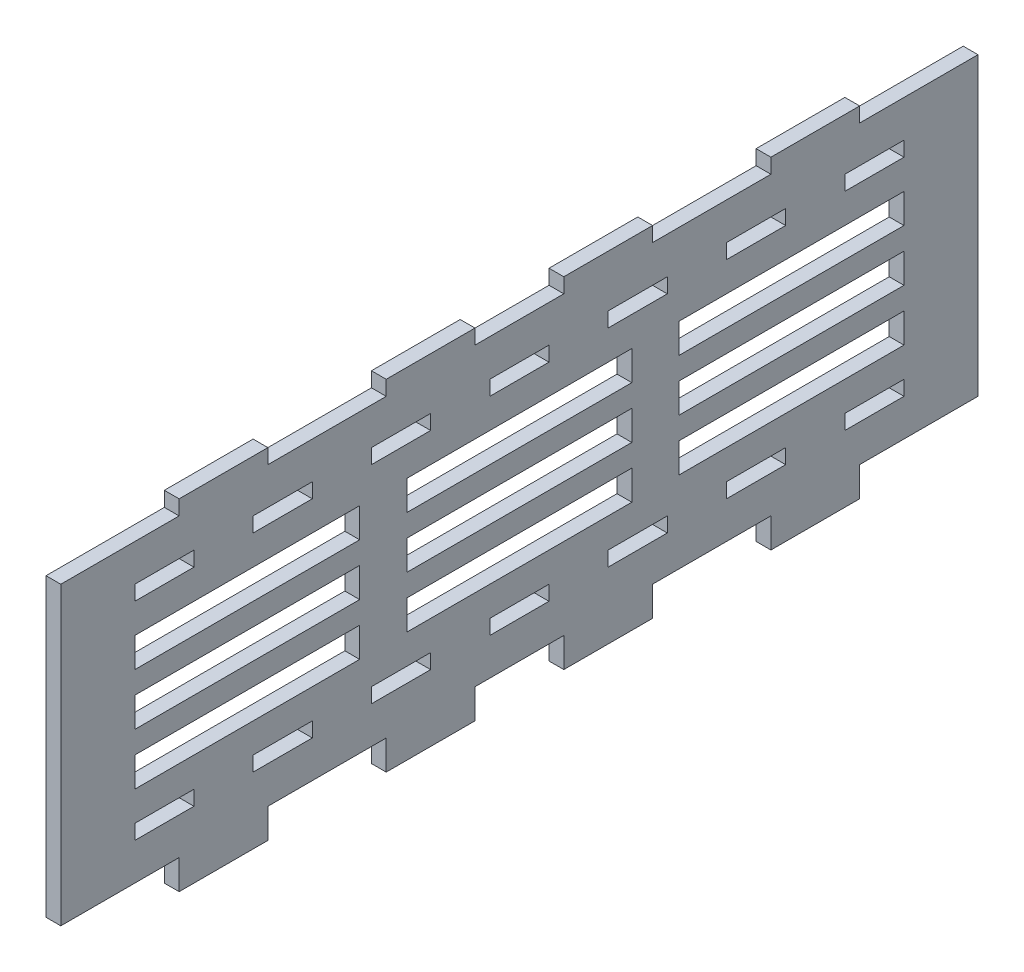
SolidWorks part; units mm, degrees
material "Maple"
ref_plane "Front Plane" through (0, 0, 0) normal (0, 0, 1) x (1, 0, 0)
ref_plane "Top Plane" through (0, 0, 0) normal (0, 1, 0) x (1, 0, 0)
ref_plane "Right Plane" through (0, 0, 0) normal (1, 0, 0) x (0, 0, -1)
sketch "Sketch1" plane through (0, 0, 0) normal (1, 0, 0) x (0, 0, -1)
  line L0 (-77.507, 27.5) -> (77.507, 27.5) construction
  line L1 (-77.507, -25) -> (77.507, -25) construction
  line L2 (-77.507, -25) -> (-77.507, 25) construction
  line L3 (-77.507, 25) -> (77.507, 25) construction
  line L4 (77.507, -25) -> (77.507, 25) construction
  line L5 (-77.507, -25) -> (77.507, 25) construction
  line L6 (-77.507, 25) -> (77.507, -25) construction
  line L7 (-77.507, -30) -> (77.507, -30) construction
  line L8 (-20.5112, 0) -> (21.2154, 0) construction
  line L9 (0, 9.427) -> (0, -9.8875) construction
  line L10 (-77.507, 25) -> (-77.507, -25)
  line L11 (-77.507, -25) -> (-57.507, -25)
  line L12 (-57.507, -25) -> (-57.507, -30)
  line L13 (-57.507, -30) -> (-42.507, -30)
  line L14 (-42.507, -30) -> (-42.507, -25)
  line L15 (-42.507, -25) -> (-22.507, -25)
  line L16 (-22.507, -25) -> (-22.507, -30)
  line L17 (-22.507, -30) -> (-7.507, -30)
  line L18 (-7.507, -30) -> (-7.507, -25)
  line L19 (-7.507, -25) -> (7.507, -25)
  line L20 (-7.507, 25) -> (7.507, 25)
  line L21 (-7.507, 27.5) -> (-7.507, 25)
  line L22 (-22.507, 27.5) -> (-7.507, 27.5)
  line L23 (-22.507, 25) -> (-22.507, 27.5)
  line L24 (-42.507, 25) -> (-22.507, 25)
  line L25 (-42.507, 27.5) -> (-42.507, 25)
  line L26 (-57.507, 27.5) -> (-42.507, 27.5)
  line L27 (-57.507, 25) -> (-57.507, 27.5)
  line L28 (-77.507, 25) -> (-57.507, 25)
  line L29 (7.507, -30) -> (7.507, -25)
  line L30 (22.507, -30) -> (7.507, -30)
  line L31 (22.507, -25) -> (22.507, -30)
  line L32 (42.507, -25) -> (22.507, -25)
  line L33 (42.507, -30) -> (42.507, -25)
  line L34 (57.507, -30) -> (42.507, -30)
  line L35 (57.507, -25) -> (57.507, -30)
  line L36 (77.507, -25) -> (57.507, -25)
  line L37 (77.507, 25) -> (77.507, -25)
  line L38 (77.507, 25) -> (57.507, 25)
  line L39 (57.507, 25) -> (57.507, 27.5)
  line L40 (57.507, 27.5) -> (42.507, 27.5)
  line L41 (42.507, 27.5) -> (42.507, 25)
  line L42 (42.507, 25) -> (22.507, 25)
  line L43 (22.507, 25) -> (22.507, 27.5)
  line L44 (22.507, 27.5) -> (7.507, 27.5)
  line L45 (7.507, 27.5) -> (7.507, 25)
  line L46 (-5, 16.25) -> (5, 16.25)
  line L51 (-65, -11.25) -> (-65, -6.25)
  line L52 (-27, -11.25) -> (-65, -11.25)
  line L57 (-27, -6.25) -> (-27, -11.25)
  line L58 (-65, -6.25) -> (-27, -6.25)
  line L59 (-5, -18.75) -> (5, -18.75)
  line L60 (-5, -18.75) -> (-5, -16.25)
  line L61 (-5, -16.25) -> (5, -16.25)
  line L62 (5, -18.75) -> (5, -16.25)
  line L63 (-5, -18.75) -> (5, -16.25) construction
  line L64 (-5, -16.25) -> (5, -18.75) construction
  line L65 (5, 18.75) -> (5, 16.25)
  line L66 (-5, 18.75) -> (5, 18.75)
  line L67 (-5, 18.75) -> (-5, 16.25)
  line L68 (-25, -18.75) -> (-25, -16.25)
  line L69 (-25, -18.75) -> (-15, -18.75)
  line L70 (-15, -18.75) -> (-15, -16.25)
  line L71 (-25, -16.25) -> (-15, -16.25)
  line L72 (-25, 16.25) -> (-15, 16.25)
  line L73 (-15, 18.75) -> (-15, 16.25)
  line L74 (-25, 18.75) -> (-15, 18.75)
  line L75 (-25, 18.75) -> (-25, 16.25)
  line L76 (-45, -18.75) -> (-45, -16.25)
  line L77 (-45, -18.75) -> (-35, -18.75)
  line L78 (-35, -18.75) -> (-35, -16.25)
  line L79 (-45, -16.25) -> (-35, -16.25)
  line L80 (-45, 16.25) -> (-35, 16.25)
  line L81 (-35, 18.75) -> (-35, 16.25)
  line L82 (-45, 18.75) -> (-35, 18.75)
  line L83 (-45, 18.75) -> (-45, 16.25)
  line L84 (-65, -18.75) -> (-65, -16.25)
  line L85 (-65, -18.75) -> (-55, -18.75)
  line L86 (-55, -18.75) -> (-55, -16.25)
  line L87 (-65, -16.25) -> (-55, -16.25)
  line L88 (-65, 16.25) -> (-55, 16.25)
  line L89 (-55, 18.75) -> (-55, 16.25)
  line L90 (-65, 18.75) -> (-55, 18.75)
  line L91 (-65, 18.75) -> (-65, 16.25)
  line L92 (15, -18.75) -> (15, -16.25)
  line L93 (15, -18.75) -> (25, -18.75)
  line L94 (25, -18.75) -> (25, -16.25)
  line L95 (15, -16.25) -> (25, -16.25)
  line L96 (15, 16.25) -> (25, 16.25)
  line L97 (25, 18.75) -> (25, 16.25)
  line L98 (15, 18.75) -> (25, 18.75)
  line L99 (15, 18.75) -> (15, 16.25)
  line L100 (35, -18.75) -> (35, -16.25)
  line L101 (35, -18.75) -> (45, -18.75)
  line L102 (45, -18.75) -> (45, -16.25)
  line L103 (35, -16.25) -> (45, -16.25)
  line L104 (35, 16.25) -> (45, 16.25)
  line L105 (45, 18.75) -> (45, 16.25)
  line L106 (35, 18.75) -> (45, 18.75)
  line L107 (35, 18.75) -> (35, 16.25)
  line L108 (55, -18.75) -> (55, -16.25)
  line L109 (55, -18.75) -> (65, -18.75)
  line L110 (65, -18.75) -> (65, -16.25)
  line L111 (55, -16.25) -> (65, -16.25)
  line L112 (55, 16.25) -> (65, 16.25)
  line L113 (65, 18.75) -> (65, 16.25)
  line L114 (55, 18.75) -> (65, 18.75)
  line L115 (55, 18.75) -> (55, 16.25)
  line L116 (19, 11.25) -> (-19, 11.25)
  line L117 (-19, 11.25) -> (-19, 6.25)
  line L118 (-19, 6.25) -> (19, 6.25)
  line L119 (19, 6.25) -> (19, 11.25)
  line L120 (65, 11.25) -> (27, 11.25)
  line L121 (27, 11.25) -> (27, 6.25)
  line L122 (27, 6.25) -> (65, 6.25)
  line L123 (65, 6.25) -> (65, 11.25)
  line L124 (65, 11.25) -> (27, 11.25)
  line L125 (27, 11.25) -> (27, 6.25)
  line L126 (27, 6.25) -> (65, 6.25)
  line L127 (65, 6.25) -> (65, 11.25)
  line L152 (-65, -2.5) -> (-27, -2.5)
  line L153 (-27, -2.5) -> (-27, 2.5)
  line L154 (-27, 2.5) -> (-65, 2.5)
  line L155 (-65, 2.5) -> (-65, -2.5)
  line L156 (-65, -2.5) -> (-27, -2.5)
  line L157 (-27, -2.5) -> (-27, 2.5)
  line L158 (-27, 2.5) -> (-65, 2.5)
  line L159 (-65, 2.5) -> (-65, -2.5)
  line L160 (-27, 11.25) -> (-65, 11.25)
  line L161 (-65, 11.25) -> (-65, 6.25)
  line L162 (-65, 6.25) -> (-27, 6.25)
  line L163 (-27, 6.25) -> (-27, 11.25)
  line L164 (-27, 11.25) -> (-65, 11.25)
  line L165 (-65, 11.25) -> (-65, 6.25)
  line L166 (-65, 6.25) -> (-27, 6.25)
  line L167 (-27, 6.25) -> (-27, 11.25)
  line L168 (65, -6.25) -> (27, -6.25)
  line L169 (27, -6.25) -> (27, -11.25)
  line L170 (27, -11.25) -> (65, -11.25)
  line L171 (65, -11.25) -> (65, -6.25)
  line L172 (65, -6.25) -> (27, -6.25)
  line L173 (27, -6.25) -> (27, -11.25)
  line L174 (27, -11.25) -> (65, -11.25)
  line L175 (65, -11.25) -> (65, -6.25)
  line L200 (65, 2.5) -> (27, 2.5)
  line L201 (27, 2.5) -> (27, -2.5)
  line L202 (27, -2.5) -> (65, -2.5)
  line L203 (65, -2.5) -> (65, 2.5)
  line L204 (65, 2.5) -> (27, 2.5)
  line L205 (27, 2.5) -> (27, -2.5)
  line L206 (27, -2.5) -> (65, -2.5)
  line L207 (65, -2.5) -> (65, 2.5)
  line L208 (-19, -2.5) -> (19, -2.5)
  line L209 (19, -2.5) -> (19, 2.5)
  line L210 (19, 2.5) -> (-19, 2.5)
  line L211 (-19, 2.5) -> (-19, -2.5)
  line L224 (-19, -11.25) -> (-19, -6.25)
  line L225 (-19, -6.25) -> (19, -6.25)
  line L226 (19, -6.25) -> (19, -11.25)
  line L227 (19, -11.25) -> (-19, -11.25)
  point P0 (0, 0)
  point P25 (-27, -18.75)
  point P33 (-77.507, 0)
  point P34 (0, -25)
  point P49 (0, 25)
  point P54 (-68.4029, -15.1308)
  point P59 (23.6902, -13.5681)
  point P66 (0, 0)
  point P71 (0, -17.5)
  dimension "D7" = 2
  dimension "D3" = 155.014
  dimension "D4" = 50
  dimension "D5" = 15
  dimension "D6" = 20
  dimension "D8" = 8
  dimension "D16" = 10
  dimension "D2" = 5
  dimension "D17" = 17.5
  dimension "D18" = 2.5
  dimension "D21" = 10
  dimension "D22" = 10
  dimension "D1" = 2.5
  dimension "D23" = 0
  dimension "D27" = 0
  dimension "D28" = 0
  dimension "D29" = 0
  dimension "D33" = 0
  dimension "D19" = 4
  dimension "D20" = 4
extrude "Boss-Extrude1" add sketch "Sketch1" along normal mid plane 2.5
